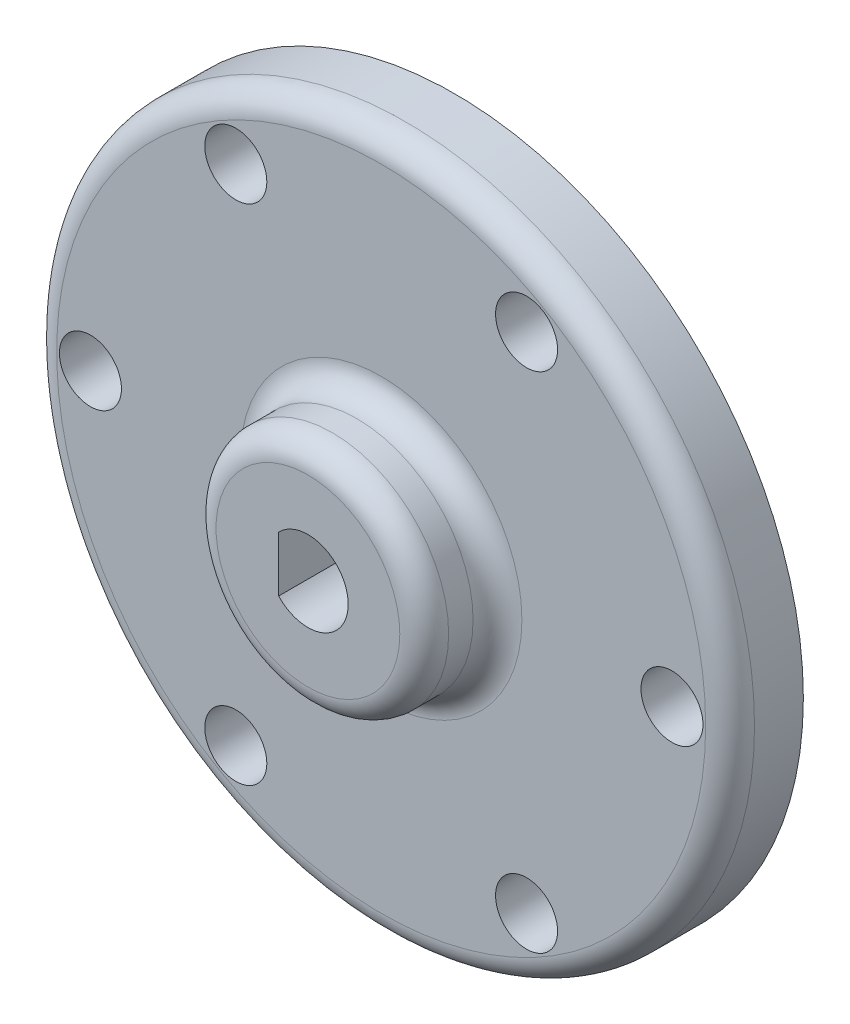
SolidWorks part; units mm, degrees
ref_plane "Front" through (0, 0, 0) normal (0, 0, 1) x (1, 0, 0)
ref_plane "Top" through (0, 0, 0) normal (0, 1, 0) x (1, 0, 0)
ref_plane "Right" through (0, 0, 0) normal (1, 0, 0) x (0, 0, -1)
sketch "Sketch1" plane through (0, 0, 0) normal (0, 0, 1) x (1, 0, 0)
  line L0 (-28.575, 0) -> (0, 0) construction
  circle A0 centre (0, 0) radius 28.575
  circle A1 centre (-23.8125, 0) radius 2.54
  circle A2 centre (-11.9062, 20.6222) radius 2.54
  circle A3 centre (11.9063, 20.6222) radius 2.54
  circle A4 centre (23.8125, 0) radius 2.54
  circle A5 centre (11.9062, -20.6222) radius 2.54
  circle A6 centre (-11.9063, -20.6222) radius 2.54
  point P19 (0, 0)
  dimension "D1" = 57.15
  dimension "D2" = 5.08
  dimension "D3" = 23.8125
  dimension "D4" = 6
extrude "Boss-Extrude1" add sketch "Sketch1" along normal mid plane 6
sketch "Sketch2" plane through (0, 0, 3) normal (0, 0, 1) x (1, 0, 0)
  circle A0 centre (0, 0) radius 9.525
  dimension "D1" = 19.05
extrude "Boss-Extrude2" add sketch "Sketch2" along normal blind 6
sketch "Sketch3" plane through (0, 0, 9) normal (0, 0, 1) x (1, 0, 0)
  line L0 (-2.4, 2.265) -> (-2.4, -2.265)
  line L1 (-2.4, 0) -> (0, 0) construction
  circle A0 centre (0, 0) radius 3.3
  dimension "D1" = 6.6
  dimension "D2" = 2.4
extrude "Cut-Extrude1" cut sketch "Sketch3" against normal up to next
fillet "Fillet1" radius 2 3 edges at (9.525, 0, 9) (9.525, 0, 3) (28.575, 0, 3)
